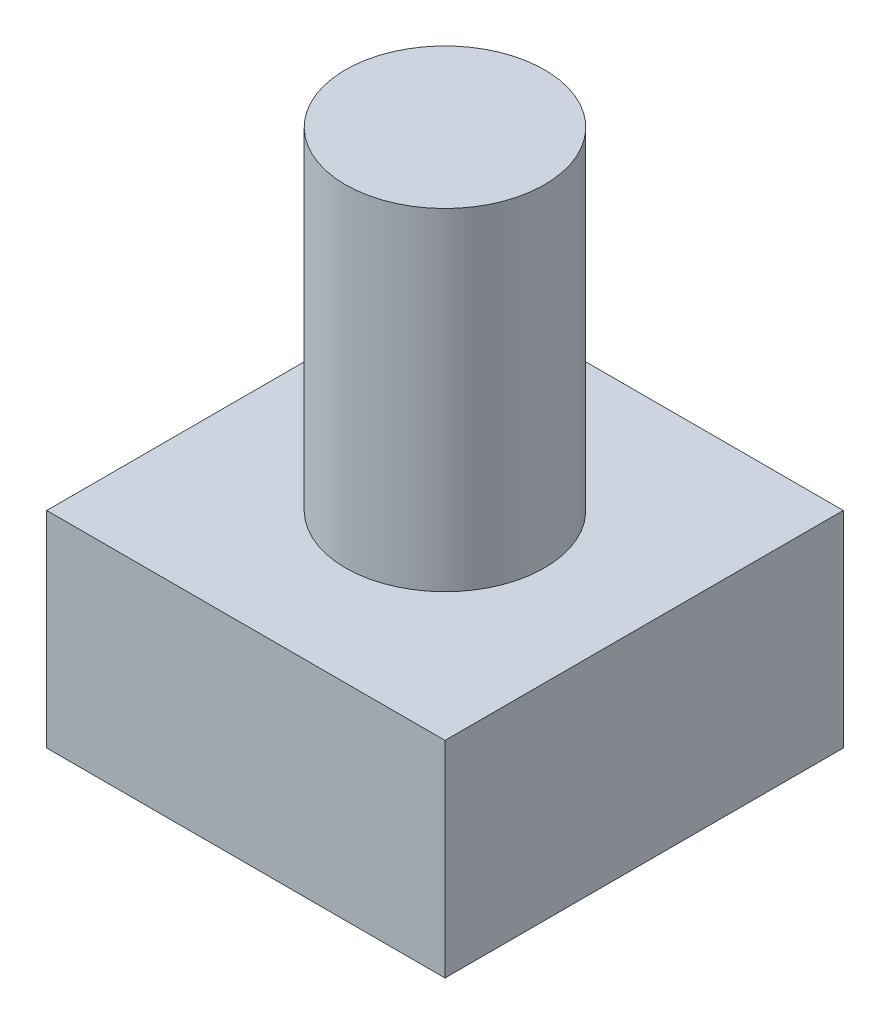
SolidWorks part; units mm, degrees
ref_plane "前视" through (0, 0, 0) normal (0, 0, 1) x (1, 0, 0)
ref_plane "上视" through (0, 0, 0) normal (0, 1, 0) x (1, 0, 0)
ref_plane "右视" through (0, 0, 0) normal (1, 0, 0) x (0, 0, -1)
sketch "草图1" plane through (0, 0, 0) normal (0, 1, 0) x (1, 0, 0)
  line L0 (0, 96.9306) -> (0, -101.3275) construction
  line L1 (-119.7143, 0) -> (134.9034, 0) construction
  line L3 (-3, 3) -> (3, 3)
  line L4 (-3, 3) -> (-3, -3)
  line L5 (-3, -3) -> (3, -3)
  line L6 (3, 3) -> (3, -3)
  dimension "D1" = 6
  dimension "D2" = 6
extrude "拉伸1" add sketch "草图1" along normal blind 3.1
sketch "草图2" plane through (0, 3.1, 0) normal (0, 1, 0) x (-1, 0, 0)
  line L0 (-3, 0) -> (8.7109, 0) construction
  line L1 (-3, 3) -> (-3, -3) construction
  line L2 (0, -7.8518) -> (0, 10.0992) construction
  circle A0 centre (0, 0) radius 1.5
  dimension "D1" = 3
extrude "拉伸2" add sketch "草图2" along normal blind 5
sketch "草图3" plane through (-3, 0, 0) normal (-1, 0, 0) x (0, 0, 1)
  line L0 (0, -6.9925) -> (0, 14.8526) construction
sketch "草图4" plane through (0, 8.1, 0) normal (0, 1, 0) x (-1, 0, 0)
  line L0 (0, -4.1469) -> (0, 4.9476) construction
  line L1 (-3.9082, 0) -> (5.1305, 0) construction
sketch "草图5" plane through (0, 0, 0) normal (0, -1, 0) x (1, 0, 0)
  line L0 (-4.4583, 0) -> (4.1341, 0) construction
  line L1 (0, 4.6756) -> (0, -4.3899) construction
